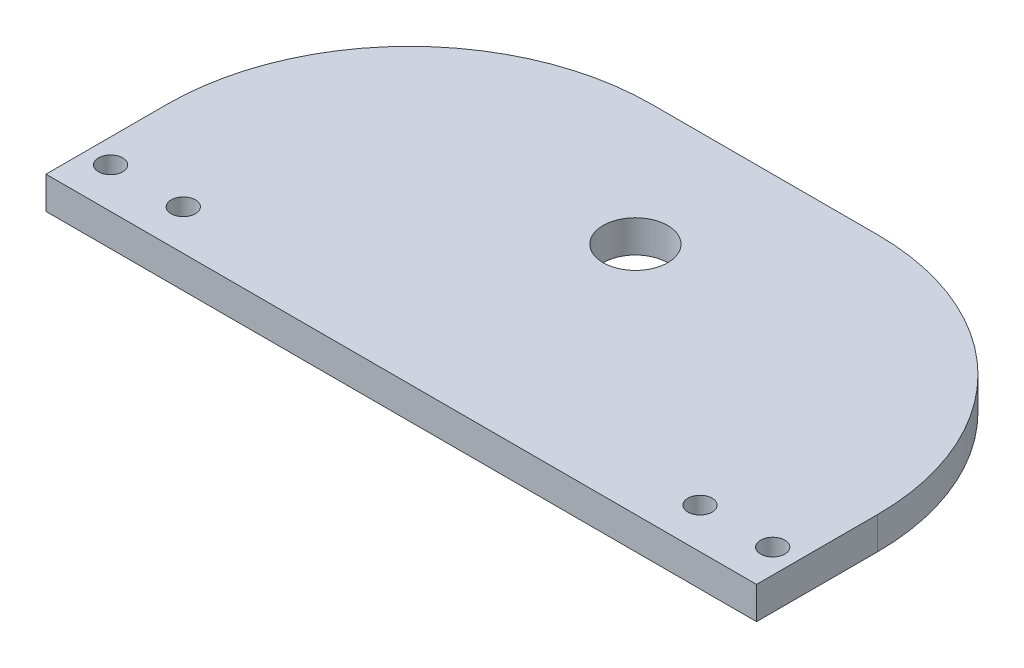
SolidWorks part; units mm, degrees
material "环氧树脂,未充填"
ref_plane "前视基准面" through (0, 0, 0) normal (0, 0, 1) x (1, 0, 0)
ref_plane "上视基准面" through (0, 0, 0) normal (0, 1, 0) x (1, 0, 0)
ref_plane "右视基准面" through (0, 0, 0) normal (1, 0, 0) x (0, 0, -1)
sketch "草图1" plane through (0, 0, 0) normal (0, 1, 0) x (1, 0, 0)
  line L1 (-44, 22.5) -> (44, 22.5)
  line L2 (-44, 22.5) -> (-44, -22.5)
  line L3 (-44, -22.5) -> (44, -22.5)
  line L4 (44, 22.5) -> (44, -22.5)
  line L5 (-44, 22.5) -> (44, -22.5) construction
  line L6 (-44, -22.5) -> (44, 22.5) construction
  point P0 (0, 0)
  dimension "D1" = 88
  dimension "D2" = 45
extrude "凸台-拉伸1" add sketch "草图1" along normal blind 4
sketch "草图2" plane through (0, 4, 0) normal (0, 1, 0) x (1, 0, 0)
  line L0 (-44, -22.5) -> (44, -22.5) construction
  circle A0 centre (0, 6.5) radius 4
  point P4 (0, 0)
  dimension "D1" = 8
  dimension "D2" = 29
extrude "切除-拉伸1" cut sketch "草图2" against normal blind 4
sketch "草图3" plane through (0, 4, 0) normal (0, 1, 0) x (1, 0, 0)
  line L0 (-36.5, -22.5) -> (-36.5, 22.5) construction
  line L1 (-44, -22.5) -> (44, -22.5) construction
  line L2 (44, 22.5) -> (-44, 22.5) construction
  line L3 (-44, 22.5) -> (-44, -22.5) construction
  line L4 (0, 22.5) -> (0, -22.5) construction
  circle A0 centre (-41, -17.5) radius 1.5
  circle A1 centre (-32, -17.5) radius 1.5
  circle A2 centre (32, -17.5) radius 1.5
  circle A3 centre (41, -17.5) radius 1.5
  dimension "D1" = 7.5
  dimension "D3" = 3
  dimension "D2" = 9
  dimension "D4" = 5
extrude "切除-拉伸2" cut sketch "草图3" against normal through all
fillet "圆角1" radius 30 2 edges at (44, 2, -22.5) (-44, 2, -22.5)
